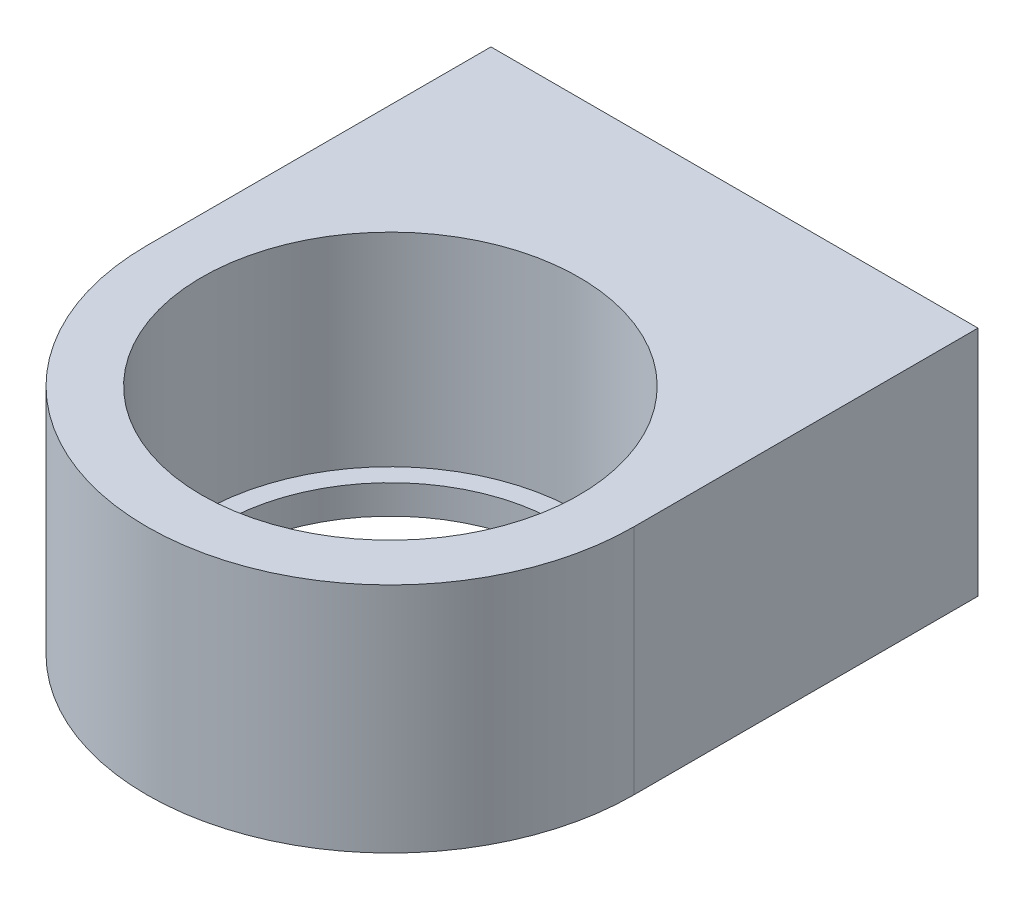
SolidWorks part; units mm, degrees
material "6061-T6 (SS)"
ref_plane "Front Plane" through (0, 0, 0) normal (0, 0, 1) x (1, 0, 0)
ref_plane "Top Plane" through (0, 0, 0) normal (0, 1, 0) x (1, 0, 0)
ref_plane "Right Plane" through (0, 0, 0) normal (1, 0, 0) x (0, 0, -1)
sketch "Sketch1" plane through (0, 0, 0) normal (0, 1, 0) x (1, 0, 0)
  line L0 (-13.3188, 0) -> (-13.3188, 13.3188)
  line L2 (13.3188, 13.3188) -> (13.3188, 0)
  line L3 (-13.3188, 13.3188) -> (-13.3188, 17.8188)
  line L4 (-13.3188, 17.8188) -> (13.3188, 17.8188)
  line L5 (13.3188, 17.8188) -> (13.3188, 13.3188)
  arc A1 (-13.3188, 0) -> (13.3188, 0) centre (0, 0) ccw
  circle A3 centre (0, 0) radius 9.25
extrude "Boss-Extrude1" add sketch "Sketch1" along normal blind 12.7
sketch "Sketch2" plane through (0, 12.7, 0) normal (0, 1, 0) x (1, 0, 0)
  circle A0 centre (0, 0) radius 10.3187
  dimension "D1" = 20.6375
extrude "Cut-Extrude1" cut sketch "Sketch2" against normal blind 11.1125
sketch "Sketch3" plane through (0, 0, -17.8188) normal (0, 0, -1) x (-1, 0, 0)
  line L0 (-13.3188, 12.7) -> (-7.8188, 12.7) construction
  line L2 (-13.3188, 12.7) -> (13.3188, 12.7) construction
  line L3 (-7.8188, 12.7) -> (-7.8188, 6.35) construction
  line L4 (13.3188, 12.7) -> (7.8188, 12.7) construction
  line L5 (7.8188, 12.7) -> (7.8188, 6.35) construction
  circle A0 centre (-7.8188, 6.35) radius 3
  circle A1 centre (7.8188, 6.35) radius 3
extrude "Cut-Extrude2" cut sketch "Sketch3" against normal blind 7.5
sketch "Sketch4" plane through (0, 0, -17.8188) normal (0, 0, -1) x (-1, 0, 0)
  line L8 (-13.3188, 0) -> (13.3188, 0)
  line L9 (13.3188, 0) -> (13.3188, 12.7)
  line L10 (13.3188, 12.7) -> (-13.3188, 12.7)
  line L11 (-13.3188, 12.7) -> (-13.3188, 0)
  line L12 (-13.3188, 0) -> (13.3188, 0)
  line L13 (13.3188, 0) -> (13.3188, 12.7)
  line L14 (13.3188, 12.7) -> (-13.3188, 12.7)
  line L15 (-13.3188, 12.7) -> (-13.3188, 0)
  circle A2 centre (-7.8188, 6.35) radius 3
  circle A3 centre (-7.8188, 6.35) radius 3
  circle A5 centre (7.8188, 6.35) radius 3
  circle A6 centre (7.8188, 6.35) radius 3
  dimension "D1" = 0
  dimension "D2" = 0
  dimension "D3" = 0
extrude "Boss-Extrude2" add sketch "Sketch4" along normal blind 1
